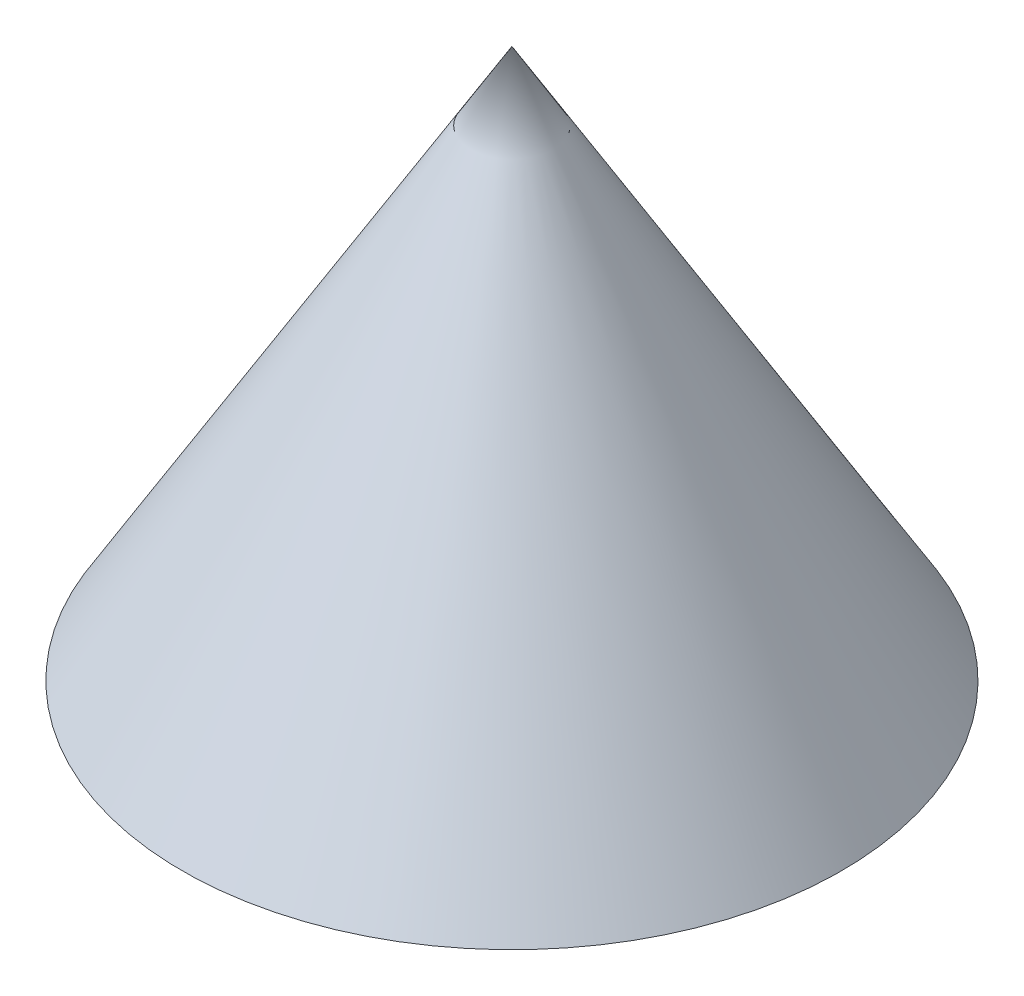
SolidWorks part; units mm, degrees
ref_plane "前视基准面" through (0, 0, 0) normal (0, 0, 1) x (1, 0, 0)
ref_plane "上视基准面" through (0, 0, 0) normal (0, 1, 0) x (1, 0, 0)
ref_plane "右视基准面" through (0, 0, 0) normal (1, 0, 0) x (0, 0, -1)
other "Configuration Table"
sketch "草图1" plane through (0, 0, 0) normal (0, 0, 1) x (1, 0, 0)
  line L0 (0, -100) -> (0, 300) construction
  line L1 (0, 0) -> (150, 0)
  line L2 (150, 0) -> (0, 250)
  line L3 (0, 250) -> (0, 0)
revolve "旋转1" add sketch "草图1" angle 360 about L0
